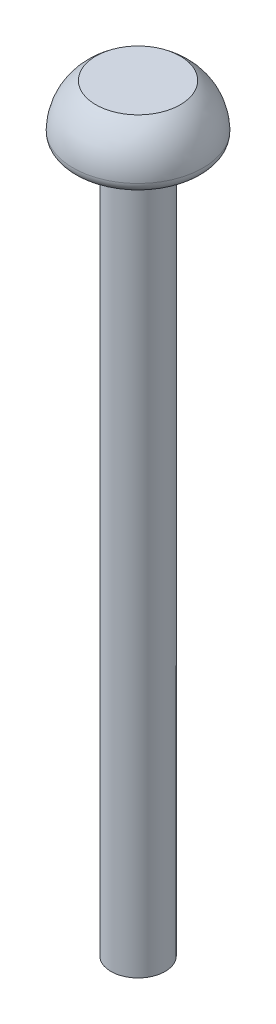
SolidWorks part; units mm, degrees
ref_plane "Plan de face" through (0, 0, 0) normal (0, 0, 1) x (1, 0, 0)
ref_plane "Plan de dessus" through (0, 0, 0) normal (0, 1, 0) x (1, 0, 0)
ref_plane "Plan de droite" through (0, 0, 0) normal (1, 0, 0) x (0, 0, -1)
sketch "Esquisse1" plane through (0, 0, 0) normal (0, 0, 1) x (1, 0, 0)
  line L0 (0, -51.4789) -> (0, 1135.3795) construction
  line L1 (0, 33.6029) -> (25, 33.6029)
  line L2 (25, 33.6029) -> (25, 683.6029)
  line L3 (25, 683.6029) -> (0, 683.6029)
  line L4 (0, 683.6029) -> (0, 33.6029)
  line L5 (0, 683.6029) -> (0, 693.6029)
  line L6 (0, 693.6029) -> (60, 693.6029)
  line L7 (0, 693.6029) -> (0, 733.6029)
  line L8 (25, 683.6029) -> (50, 683.6029)
  line L9 (0, 733.6029) -> (38.9656, 733.6029)
  line L10 (8, 33.6029) -> (8, 83.6029)
  line L11 (0, 83.6029) -> (8, 83.6029)
  arc A0 (50, 683.6029) -> (60, 693.6029) centre (50, 693.6029) ccw
  arc A2 (60, 693.6029) -> (38.9656, 733.6029) centre (10.0058, 692.8434) ccw
  point P7 (0, 688.6029)
  dimension "D7" = 20
  dimension "D9" = 100
  dimension "D11" = 10.0058
  dimension "D1" = 51.4789
  dimension "D2" = 25
  dimension "D3" = 650
  dimension "D4" = 33.6029
  dimension "D5" = 50
  dimension "D6" = 60
  dimension "D8" = 50
  dimension "D10" = 10
  dimension "D12" = 50
  dimension "D13" = 8
  dimension "D14" = 0
  dimension "D15" = 8
revolve "Révolution1" add sketch "Esquisse1" angle 360 about L0
